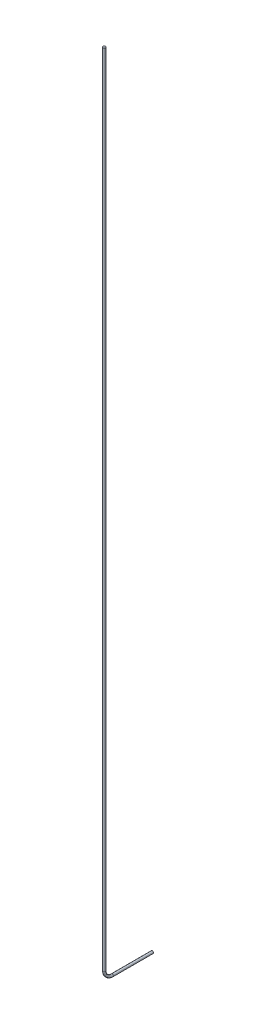
SolidWorks part; units mm, degrees
ref_plane "正面" through (0, 0, 0) normal (0, 0, 1) x (1, 0, 0)
ref_plane "平面" through (0, 0, 0) normal (0, 1, 0) x (1, 0, 0)
ref_plane "右側面" through (0, 0, 0) normal (1, 0, 0) x (0, 0, -1)
sketch "ｽｹｯﾁ1" plane through (0, 0, 0) normal (0, 0, 1) x (1, 0, 0)
  circle A0 centre (0, 0) radius 0.75
  dimension "D1" = 1.5
extrude "ﾎﾞｽ - 押し出し1" add sketch "ｽｹｯﾁ1" along normal blind 20
sketch "ｽｹｯﾁ2" plane through (0, 0, 20) normal (0, 0, 1) x (1, 0, 0)
  circle A1 centre (0, 0) radius 0.75
  circle A2 centre (0, 0) radius 0.75
  point P0 (0, 0)
  dimension "D1" = 0
sketch "ｽｹｯﾁ3" plane through (0, 0, 0) normal (1, 0, 0) x (0, 0, -1)
  line L0 (-20, 0) -> (-25, 0)
  line L1 (-20, 0.75) -> (-20, -0.75) construction
  line L2 (-30, 5) -> (-30, 505)
  line L3 (-20, 0.75) -> (-20, -0.75) construction
  arc A0 (-25, 0) -> (-30, 5) centre (-25, 5) cw
  point P8 (-30, 0)
  point P9 (0, 0)
  point P10 (0, 0)
  dimension "D2" = 5
  dimension "D1" = 10
  dimension "D3" = 500
sweep "ｽｲｰﾌﾟ1" add profiles "ｽｹｯﾁ2" path "ｽｹｯﾁ3"
